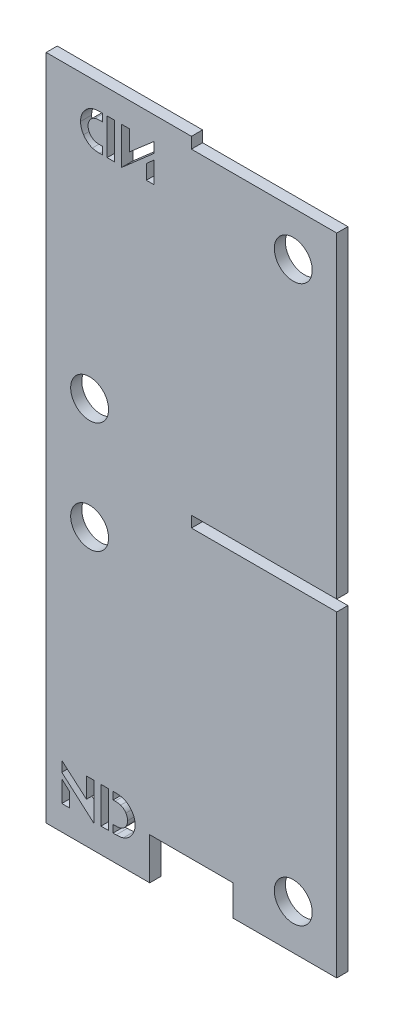
SolidWorks part; units mm, degrees
ref_plane "Front Plane" through (0, 0, 0) normal (0, 0, 1) x (1, 0, 0)
ref_plane "Top Plane" through (0, 0, 0) normal (0, 1, 0) x (1, 0, 0)
ref_plane "Right Plane" through (0, 0, 0) normal (1, 0, 0) x (0, 0, -1)
sketch "Sketch1" plane through (0, 0, 0) normal (0, 0, 1) x (1, 0, 0)
  line L1 (66.3575, -152.4) -> (-66.3575, -152.4)
  line L2 (66.3575, -152.4) -> (66.3575, 152.4)
  line L3 (66.3575, 152.4) -> (-66.3575, 152.4)
  line L4 (-66.3575, -152.4) -> (-66.3575, 152.4)
  line L5 (66.3575, -152.4) -> (-66.3575, 152.4) construction
  line L6 (66.3575, 152.4) -> (-66.3575, -152.4) construction
  point P0 (0, 0)
  dimension "D1" = 304.8
  dimension "D2" = 132.715
sketch "Sketch3" plane through (0, 0, 0) normal (0, 0, 1) x (1, 0, 0)
  line L0 (66.3575, -152.4) -> (-66.3575, -152.4) construction
  line L1 (0, -2.54) -> (66.3575, -2.54)
  line L2 (0, -2.54) -> (0, 2.54)
  line L3 (0, 2.54) -> (66.3575, 2.54)
  line L4 (66.3575, -2.54) -> (66.3575, 2.54)
  line L5 (0, -2.54) -> (66.3575, 2.54) construction
  line L6 (0, 2.54) -> (66.3575, -2.54) construction
  line L7 (-19.05, -171.45) -> (19.05, -171.45)
  line L8 (-19.05, -171.45) -> (-19.05, -133.35)
  line L9 (-19.05, -133.35) -> (19.05, -133.35)
  line L10 (19.05, -171.45) -> (19.05, -133.35)
  line L11 (-19.05, -171.45) -> (19.05, -133.35) construction
  line L12 (-19.05, -133.35) -> (19.05, -171.45) construction
  line L13 (19.05, -152.4) -> (19.05, -147.32)
  line L14 (19.05, -152.4) -> (66.3575, -152.4)
  line L15 (19.05, -147.32) -> (66.3575, -147.32)
  line L16 (66.3575, -152.4) -> (66.3575, -147.32)
  line L17 (66.3575, -152.4) -> (66.3575, 152.4) construction
  line L18 (0, 152.4) -> (0, 147.32)
  line L19 (0, 152.4) -> (76.2, 152.4)
  line L20 (0, 147.32) -> (76.2, 147.32)
  line L21 (76.2, 152.4) -> (76.2, 147.32)
  line L22 (66.3575, 152.4) -> (-66.3575, 152.4) construction
  point P0 (33.1788, 0)
  point P5 (0, -152.4)
  dimension "D1" = 33.1788
  dimension "D2" = 66.3575
  dimension "D3" = 5.08
  dimension "D4" = 38.1
  dimension "D5" = 38.1
  dimension "D6" = 5.08
  dimension "D7" = 5.08
  dimension "D8" = 76.2
extrude "Boss-Extrude1" add sketch "Sketch1" along normal blind 5.08
extrude "Cut-Extrude1" cut sketch "Sketch3" along normal up to next contours L7 L10 L9 L8 | L15 L16 L14 L13 | L1 L4 L3 L2 | L20 L21 L19 L18
sketch "Sketch4" plane through (0, 0, 5.08) normal (0, 0, 1) x (1, 0, 0)
  line L0 (0, 0) -> (-66.3575, 0) construction
  line L1 (-66.3575, 152.4) -> (-66.3575, -152.4) construction
  line L2 (-66.3575, 76.2) -> (66.3575, 76.2) construction
  line L3 (66.3575, 2.54) -> (66.3575, 147.32) construction
  line L4 (-66.3575, -76.2) -> (66.3575, -76.2) construction
  line L5 (0, 152.4) -> (0, -133.35) construction
  line L6 (-19.05, -133.35) -> (19.05, -133.35) construction
  circle A0 centre (-46.5027, 25.4) radius 8.661
  circle A1 centre (-46.5027, -25.4) radius 8.661
  circle A4 centre (46.5027, -127) radius 8.661
  circle A5 centre (46.5027, 127) radius 8.661
  dimension "D1" = 25.4
  dimension "D2" = 76.2
extrude "Cut-Extrude2" cut sketch "Sketch4" against normal up to next
sketch "Sketch5" plane through (0, 0, 0) normal (0, 0, -1) x (-1, 0, 0)
  line L0 (17.1632, 124.7111) -> (17.1632, 134.4318)
  line L1 (17.1632, 134.4318) -> (20.6029, 131.3218)
  line L2 (20.6029, 131.3218) -> (20.6029, 124.7111)
  line L3 (20.6029, 124.7111) -> (17.1632, 124.7111)
  line L4 (17.1632, 137.0475) -> (17.1632, 141.7556)
  line L5 (17.1632, 141.7556) -> (28.3996, 132.0061)
  line L6 (28.3996, 132.0061) -> (28.3996, 141.2217)
  line L7 (28.3996, 141.2217) -> (31.8393, 141.2217)
  line L8 (31.8393, 141.2217) -> (31.8393, 124.1808)
  line L9 (31.8393, 124.1808) -> (17.1632, 137.0475)
  line L10 (35.0497, 124.7111) -> (35.0497, 141.2217)
  line L11 (35.0497, 141.2217) -> (38.4894, 141.2217)
  line L12 (38.4894, 141.2217) -> (38.4894, 124.7111)
  line L13 (38.4894, 124.7111) -> (35.0497, 124.7111)
  line L14 (40.5533, 124.7111) -> (40.5533, 128.1508)
  line L15 (40.5533, 128.1508) -> (41.8467, 128.1508)
  line L16 (41.4598, 137.782) -> (40.5533, 137.782)
  line L17 (40.5533, 137.782) -> (40.5533, 141.2217)
  line L18 (40.5533, 141.2217) -> (41.8216, 141.2217)
  line L19 (41.9686, 124.7111) -> (40.5533, 124.7111)
  spline S0 degree 3 poles (41.8467, 128.1508) (42.3006, 128.1499) (43.1102, 128.1924) (43.9054, 128.3594) (44.2366, 128.4912) knots 0 0 0 0 0.561163 1 1 1 1
  spline S1 degree 3 poles (44.2366, 128.4912) (44.4725, 128.5895) (44.8209, 128.7528) (45.243, 129.0405) (45.5458, 129.2749) (45.8261, 129.5428) (46.1799, 129.9423) (46.4154, 130.2728) (46.5548, 130.5084) knots 0 0 0 0 0.245408 0.366698 0.488993 0.612079 0.737762 1 1 1 1
  spline S2 degree 3 poles (46.5548, 130.5084) (46.7656, 130.871) (47.1011, 131.654) (47.205, 132.4998) (47.2034, 132.9234) knots 0 0 0 0 0.497557 1 1 1 1
  spline S3 degree 3 poles (47.2034, 132.9234) (47.209, 133.3933) (47.0759, 134.326) (46.6861, 135.1834) (46.433, 135.5712) knots 0 0 0 0 0.503604 1 1 1 1
  spline S4 degree 3 poles (46.433, 135.5712) (46.2885, 135.798) (46.0457, 136.1148) (45.6813, 136.4956) (45.391, 136.7513) (45.0773, 136.9762) (44.6357, 137.2472) (44.277, 137.4027) (44.0324, 137.4918) knots 0 0 0 0 0.257366 0.381148 0.504363 0.627238 0.750443 1 1 1 1
  spline S5 degree 3 poles (44.0324, 137.4918) (43.8769, 137.5455) (43.6238, 137.6079) (43.2664, 137.6697) (42.9584, 137.7143) (42.6235, 137.7453) (42.1206, 137.7734) (41.7298, 137.7845) (41.4598, 137.782) knots 0 0 0 0 0.189708 0.300315 0.418659 0.548841 0.688327 1 1 1 1
  spline S6 degree 3 poles (41.8216, 141.2217) (42.45, 141.219) (43.6225, 141.1581) (44.7688, 140.899) (45.2793, 140.7165) knots 0 0 0 0 0.537427 1 1 1 1
  spline S7 degree 3 poles (45.2793, 140.7165) (45.6641, 140.5831) (46.2246, 140.3323) (46.9211, 139.9055) (47.4231, 139.5456) (47.9005, 139.1398) (48.5104, 138.5277) (48.919, 138.0138) (49.174, 137.653) knots 0 0 0 0 0.242522 0.364141 0.485936 0.610069 0.736812 1 1 1 1
  spline S8 degree 3 poles (49.174, 137.653) (49.4145, 137.3091) (49.7351, 136.7685) (50.0758, 136.01) (50.2865, 135.4312) (50.4425, 134.8368) (50.5972, 134.0207) (50.647, 133.3945) (50.6431, 132.9735) knots 0 0 0 0 0.252619 0.377177 0.500231 0.623025 0.746708 1 1 1 1
  spline S9 degree 3 poles (50.6431, 132.9735) (50.6451, 132.5646) (50.5974, 131.9556) (50.4629, 131.1574) (50.3081, 130.5781) (50.1203, 130.0088) (49.8003, 129.266) (49.5065, 128.7312) (49.2815, 128.3908) knots 0 0 0 0 0.252737 0.377247 0.500185 0.623319 0.747794 1 1 1 1
  spline S10 degree 3 poles (49.2815, 128.3908) (49.0305, 128.0048) (48.616, 127.4607) (47.9897, 126.8142) (47.4985, 126.3821) (46.9774, 126.0018) (46.2442, 125.5571) (45.6526, 125.3007) (45.247, 125.159) knots 0 0 0 0 0.262241 0.388281 0.512172 0.634355 0.755219 1 1 1 1
  spline S11 degree 3 poles (45.247, 125.159) (44.7631, 124.9956) (43.6751, 124.7669) (42.5657, 124.7135) (41.9686, 124.7111) knots 0 0 0 0 0.460501 1 1 1 1
extrude "Cut-Extrude3" cut sketch "Sketch5" against normal up to next
sketch "Sketch6" plane through (0, 0, 5.08) normal (0, 0, 1) x (1, 0, 0)
  line L0 (-59.1968, -141.0777) -> (-59.1968, -131.357)
  line L1 (-59.1968, -131.357) -> (-55.7571, -134.467)
  line L2 (-55.7571, -134.467) -> (-55.7571, -141.0777)
  line L3 (-55.7571, -141.0777) -> (-59.1968, -141.0777)
  line L4 (-59.1968, -128.7413) -> (-59.1968, -124.0332)
  line L5 (-59.1968, -124.0332) -> (-47.9604, -133.7827)
  line L6 (-47.9604, -133.7827) -> (-47.9604, -124.5671)
  line L7 (-47.9604, -124.5671) -> (-44.5207, -124.5671)
  line L8 (-44.5207, -124.5671) -> (-44.5207, -141.608)
  line L9 (-44.5207, -141.608) -> (-59.1968, -128.7413)
  line L10 (-41.3103, -141.0777) -> (-41.3103, -124.5671)
  line L11 (-41.3103, -124.5671) -> (-37.8706, -124.5671)
  line L12 (-37.8706, -124.5671) -> (-37.8706, -141.0777)
  line L13 (-37.8706, -141.0777) -> (-41.3103, -141.0777)
  line L14 (-35.8068, -141.0777) -> (-35.8068, -137.638)
  line L15 (-35.8068, -137.638) -> (-34.5133, -137.638)
  line L16 (-34.9003, -128.0068) -> (-35.8068, -128.0068)
  line L17 (-35.8068, -128.0068) -> (-35.8068, -124.5671)
  line L18 (-35.8068, -124.5671) -> (-34.5384, -124.5671)
  line L19 (-34.3915, -141.0777) -> (-35.8068, -141.0777)
  spline S0 degree 3 poles (-34.5133, -137.638) (-34.0594, -137.6389) (-33.2498, -137.5964) (-32.4546, -137.4294) (-32.1234, -137.2976) knots 0 0 0 0 0.561163 1 1 1 1
  spline S1 degree 3 poles (-32.1234, -137.2976) (-31.8875, -137.1993) (-31.5391, -137.036) (-31.117, -136.7483) (-30.8142, -136.5139) (-30.5339, -136.246) (-30.1802, -135.8465) (-29.9446, -135.516) (-29.8052, -135.2804) knots 0 0 0 0 0.245408 0.366698 0.488993 0.612079 0.737762 1 1 1 1
  spline S2 degree 3 poles (-29.8052, -135.2804) (-29.5944, -134.9178) (-29.2589, -134.1348) (-29.155, -133.289) (-29.1566, -132.8654) knots 0 0 0 0 0.497557 1 1 1 1
  spline S3 degree 3 poles (-29.1566, -132.8654) (-29.151, -132.3956) (-29.2841, -131.4628) (-29.6739, -130.6054) (-29.927, -130.2176) knots 0 0 0 0 0.503604 1 1 1 1
  spline S4 degree 3 poles (-29.927, -130.2176) (-30.0715, -129.9908) (-30.3143, -129.674) (-30.6788, -129.2932) (-30.969, -129.0375) (-31.2827, -128.8126) (-31.7243, -128.5416) (-32.083, -128.3861) (-32.3276, -128.297) knots 0 0 0 0 0.257366 0.381148 0.504363 0.627238 0.750443 1 1 1 1
  spline S5 degree 3 poles (-32.3276, -128.297) (-32.4831, -128.2433) (-32.7362, -128.1809) (-33.0936, -128.1191) (-33.4016, -128.0745) (-33.7365, -128.0435) (-34.2394, -128.0154) (-34.6302, -128.0044) (-34.9003, -128.0068) knots 0 0 0 0 0.189708 0.300315 0.418659 0.548841 0.688327 1 1 1 1
  spline S6 degree 3 poles (-34.5384, -124.5671) (-33.91, -124.5698) (-32.7375, -124.6307) (-31.5912, -124.8898) (-31.0807, -125.0723) knots 0 0 0 0 0.537427 1 1 1 1
  spline S7 degree 3 poles (-31.0807, -125.0723) (-30.6959, -125.2057) (-30.1354, -125.4565) (-29.4389, -125.8833) (-28.9369, -126.2432) (-28.4596, -126.649) (-27.8497, -127.2611) (-27.441, -127.775) (-27.186, -128.1358) knots 0 0 0 0 0.242522 0.364141 0.485936 0.610069 0.736812 1 1 1 1
  spline S8 degree 3 poles (-27.186, -128.1358) (-26.9455, -128.4797) (-26.6249, -129.0203) (-26.2842, -129.7788) (-26.0735, -130.3577) (-25.9175, -130.952) (-25.7628, -131.7681) (-25.713, -132.3943) (-25.7169, -132.8153) knots 0 0 0 0 0.252619 0.377177 0.500231 0.623025 0.746708 1 1 1 1
  spline S9 degree 3 poles (-25.7169, -132.8153) (-25.7149, -133.2242) (-25.7626, -133.8332) (-25.8971, -134.6314) (-26.0519, -135.2107) (-26.2397, -135.78) (-26.5598, -136.5228) (-26.8535, -137.0576) (-27.0785, -137.398) knots 0 0 0 0 0.252737 0.377247 0.500185 0.623319 0.747794 1 1 1 1
  spline S10 degree 3 poles (-27.0785, -137.398) (-27.3296, -137.784) (-27.744, -138.3281) (-28.3703, -138.9746) (-28.8615, -139.4067) (-29.3826, -139.787) (-30.1159, -140.2317) (-30.7074, -140.4881) (-31.113, -140.6299) knots 0 0 0 0 0.262241 0.388281 0.512172 0.634355 0.755219 1 1 1 1
  spline S11 degree 3 poles (-31.113, -140.6299) (-31.597, -140.7932) (-32.6849, -141.0219) (-33.7943, -141.0753) (-34.3915, -141.0777) knots 0 0 0 0 0.460501 1 1 1 1
extrude "Cut-Extrude4" cut sketch "Sketch6" against normal up to next
